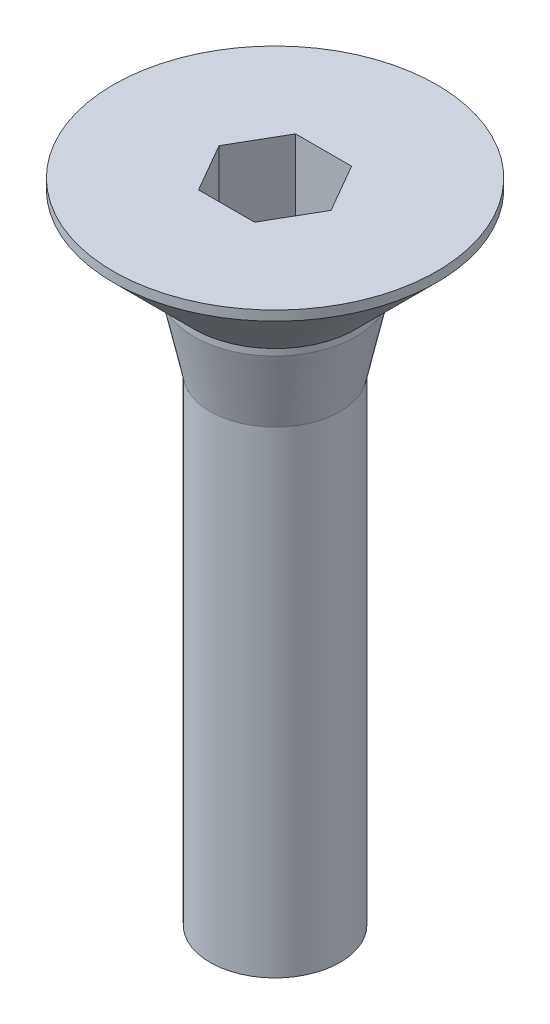
SolidWorks part; units mm, degrees
ref_plane "Vorne" through (0, 0, 0) normal (0, 0, 1) x (1, 0, 0)
ref_plane "Oben" through (0, 0, 0) normal (0, 1, 0) x (1, 0, 0)
ref_plane "Rechts" through (0, 0, 0) normal (1, 0, 0) x (0, 0, -1)
sketch "Skizze1" plane through (0, 0, 0) normal (0, 0, 1) x (1, 0, 0)
  line L0 (0, 0) -> (5, 0)
  line L1 (5, 0) -> (5, -0.3)
  line L2 (5, -0.3) -> (2.5, -2.8)
  line L3 (2.5, -2.8) -> (2.5, -3)
  line L4 (2.5, -3) -> (2.0095, -5.25)
  line L5 (2.0095, -5.25) -> (2.0095, -20)
  line L6 (2.0095, -20) -> (0, -20)
  line L7 (0, -20) -> (0, 0)
  line L8 (0, 0) -> (0, -20) construction
  dimension "DK" = 4.019
  dimension "D2" = 45
  dimension "DG" = 5
  dimension "DA" = 10
  dimension "K" = 2.8
  dimension "LS" = 3
  dimension "LG" = 5.25
  dimension "L" = 20
revolve "Basis-Rotation" add sketch "Skizze1" angle 360 about L8
sketch "Skizze2" plane through (0, 0, 0) normal (0, 1, 0) x (-1, 0, 0)
  line L0 (1.7321, 0) -> (-1.7321, 0) construction
  line L1 (0, 1.5) -> (0, -1.5) construction
  line L2 (0.866, -1.5) -> (-0.866, -1.5)
  line L3 (-0.866, -1.5) -> (-1.7321, 0)
  line L4 (0.866, -1.5) -> (1.7321, 0)
  line L5 (0.866, 1.5) -> (1.7321, 0)
  line L6 (-0.866, 1.5) -> (-1.7321, 0)
  line L7 (0.866, 1.5) -> (-0.866, 1.5)
  dimension "D2" = 120
extrude "Schnitt-Linear austragen1" cut sketch "Skizze2" against normal blind 5.3
